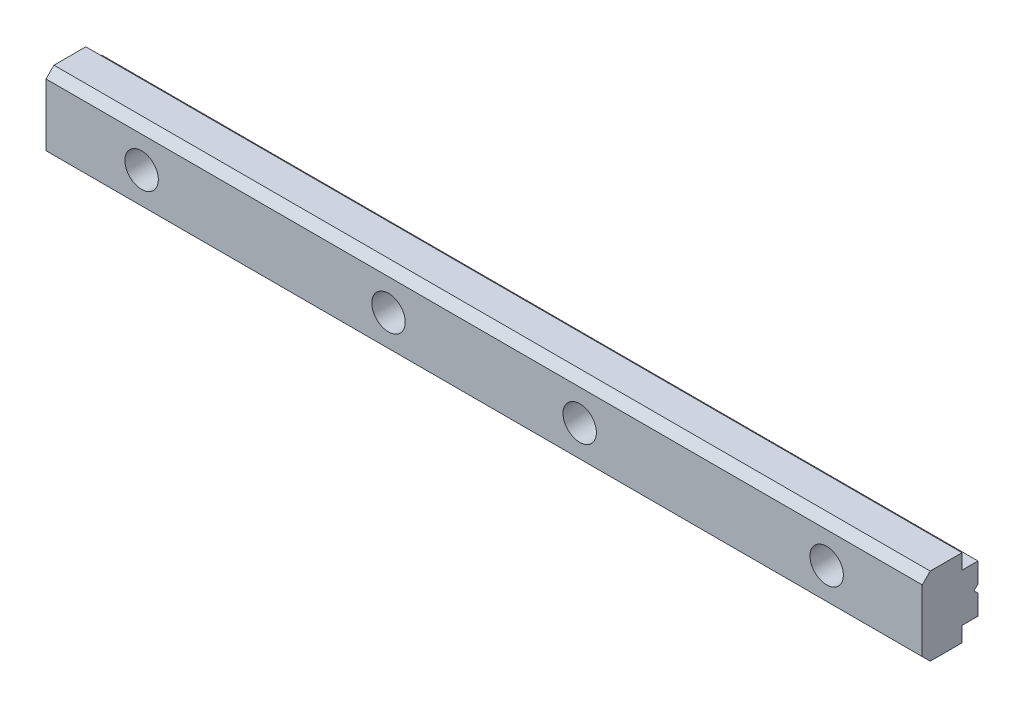
SolidWorks part; units mm, degrees
ref_plane "前视基准面" through (0, 0, 0) normal (0, 0, 1) x (1, 0, 0)
ref_plane "上视基准面" through (0, 0, 0) normal (0, 1, 0) x (1, 0, 0)
ref_plane "右视基准面" through (0, 0, 0) normal (1, 0, 0) x (0, 0, -1)
sketch "草图1" plane through (0, 0, 0) normal (1, 0, 0) x (0, 0, -1)
  line B0 (-7, -0.9) -> (-7, 6.9)
  line B1 (0, 0) -> (0, 2.5)
  line B2 (0, 3.5) -> (0, 6)
  line B3 (-2, 7.9) -> (-6, 7.9)
  line B4 (-2, -1.9) -> (-6, -1.9)
  line B5 (-2, 7.9) -> (-2, 6)
  line B6 (-2, 0) -> (-2, -1.9)
  line B7 (0, 6) -> (-2, 6)
  line B8 (0, 0) -> (-2, 0)
  line B9 (-6, -1.9) -> (-7, -0.9)
  line B10 (-6, 7.9) -> (-7, 6.9)
  line B11 (-0.5, 3) -> (0, 3.5)
  line B12 (-0.5, 3) -> (0, 2.5)
sketch_block_instance "A$C7B2C1948-1"
sketch_block "A$C7B2C1948"
extrude "凸台-拉伸1" add sketch "草图1" along normal mid plane 110
sketch "草图4" plane through (0, 0, 0) normal (0, 0, -1) x (-1, 0, 0)
  line L0 (-55, 3) -> (55, 3) construction
  line L1 (0, 7.9) -> (0, -1.9) construction
  line L2 (-55, 7.9) -> (55, 7.9) construction
  line L3 (-55, -1.9) -> (55, -1.9) construction
  point P0 (-12, 3)
  point P9 (-43, 3)
  point P10 (43, 3)
  point P11 (12, 3)
  dimension "D1" = 12
  dimension "D2" = 43
hole_wizard "M5 螺纹孔1" positions "3D草图1" profile "草图5" tap size "M5" standard "Iso"
sketch3d "3D草图1"
  point P0 (43, 3, 0)
  point P5 (12, 3, 0)
  point P7 (-12, 3, 0)
  point P9 (-43, 3, 0)
sketch "草图5" plane through (43, 3, 0) normal (1, 0, 0) x (0, 1, 0)
  line L0 (0, 0) -> (0, 53.6618)
  line L1 (0, 53.6618) -> (2.1, 52.4)
  line L2 (2.1, 52.4) -> (2.1, 0)
  line L5 (2.1, 0) -> (0, 0)
  line L10 (0, 53.6618) -> (-2.1, 52.4) construction
  line L11 (0, -6.35) -> (0, 107.95) construction
  dimension "螺纹孔钻头直径" = 4.2
  dimension "螺纹孔钻头深度" = 52.4
  dimension "导头角度" = 118
cosmetic thread "孔螺蚊线1"
cosmetic thread "孔螺蚊线2"
cosmetic thread "孔螺蚊线3"
cosmetic thread "孔螺蚊线4"
